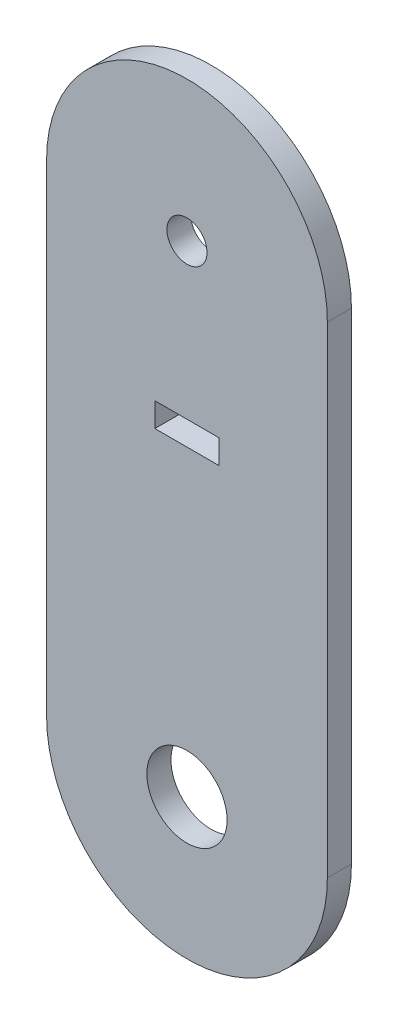
SolidWorks part; units mm, degrees
ref_plane "Alzado" through (0, 0, 0) normal (0, 0, 1) x (1, 0, 0)
ref_plane "Planta" through (0, 0, 0) normal (0, 1, 0) x (1, 0, 0)
ref_plane "Vista lateral" through (0, 0, 0) normal (1, 0, 0) x (0, 0, -1)
sketch "Croquis1" plane through (0, 0, 0) normal (0, 0, 1) x (1, 0, 0)
  line L1 (-17.5, -30) -> (17.5, -30) construction
  line L2 (-17.5, -30) -> (-17.5, 30)
  line L3 (-17.5, 30) -> (17.5, 30) construction
  line L4 (17.5, -30) -> (17.5, 30)
  line L5 (-17.5, -30) -> (17.5, 30) construction
  line L6 (-17.5, 30) -> (17.5, -30) construction
  arc A0 (-17.5, 30) -> (17.5, 30) centre (0, 30) cw
  circle A1 centre (0, 30) radius 2.5
  arc A2 (17.5, -30) -> (-17.5, -30) centre (0, -30) cw
  circle A3 centre (0, -30) radius 5
  point P0 (0, 0)
  dimension "D3" = 5
  dimension "D4" = 10
  dimension "D1" = 60
  dimension "D2" = 35
extrude "Saliente-Extruir1" add sketch "Croquis1" along normal blind 3 contours L2 A0 L4 A2
sketch "Croquis3" plane through (0, 0, 3) normal (0, 0, 1) x (1, 0, 0)
  circle A0 centre (0, 30) radius 2.5
  circle A1 centre (0, -30) radius 5
  dimension "D1" = 5
  dimension "D2" = 10
extrude "Cortar-Extruir1" cut sketch "Croquis3" against normal up to next
sketch "Croquis4" plane through (0, 0, 3) normal (0, 0, 1) x (1, 0, 0)
  line L0 (-17.5, 10.76) -> (17.5, 10.76) construction
  line L1 (-17.5, -30) -> (-17.5, 30) construction
  line L2 (17.5, -30) -> (17.5, 30) construction
  line L3 (0, -30) -> (0, 47.5) construction
  line L4 (-4, 10.76) -> (4, 10.76)
  line L5 (-4, 10.76) -> (-4, 7.76)
  line L6 (-4, 7.76) -> (4, 7.76)
  line L7 (4, 10.76) -> (4, 7.76)
  arc A0 (17.5, 30) -> (-17.5, 30) centre (0, 30) ccw construction
  point P6 (0, 30)
  point P14 (0, 0)
  point P15 (0, -30)
  dimension "D1" = 19.24
  dimension "D2" = 8
  dimension "D3" = 3
extrude "Cortar-Extruir2" cut sketch "Croquis4" against normal up to next and the other way through all
